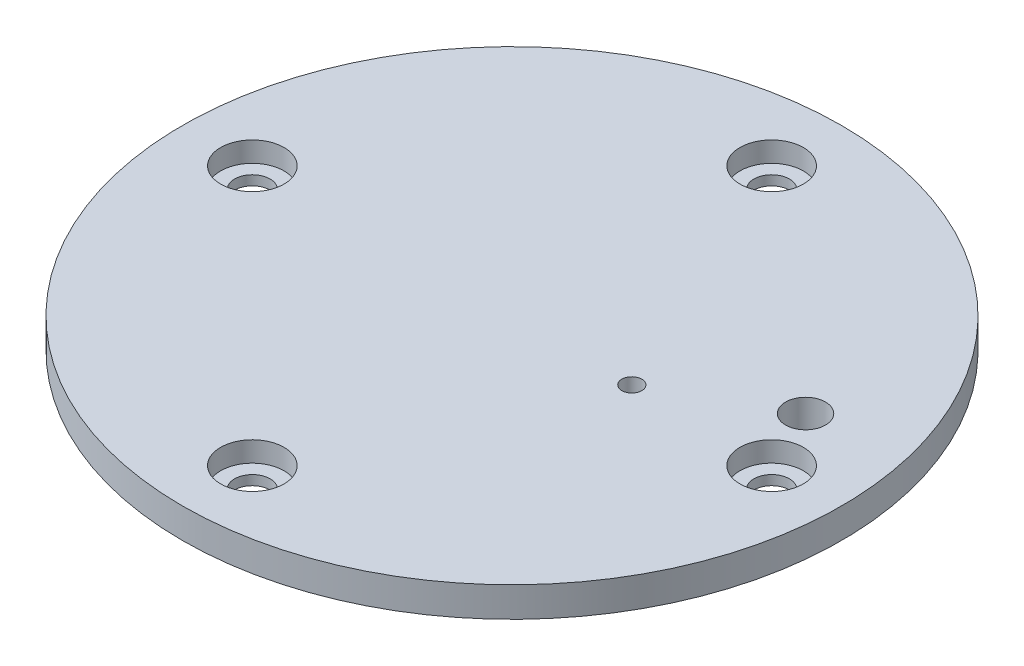
SolidWorks part; units mm, degrees
material "6061-T6 (SS)"
ref_plane "Front Plane" through (0, 0, 0) normal (0, 0, 1) x (1, 0, 0)
ref_plane "Top Plane" through (0, 0, 0) normal (0, 1, 0) x (1, 0, 0)
ref_plane "Right Plane" through (0, 0, 0) normal (1, 0, 0) x (0, 0, -1)
sketch "Sketch1" plane through (0, 0, 0) normal (0, 1, 0) x (1, 0, 0)
  circle A0 centre (0, 0) radius 16.5
  dimension "D1" = 33
extrude "Boss-Extrude1" add sketch "Sketch1" along normal blind 1.5
sketch "Sketch7" plane through (0, 1.5, 0) normal (0, 1, 0) x (1, 0, 0)
  circle A0 centre (0, -10.25) radius 0.25
  circle A1 centre (0, 0) radius 9.8
  dimension "D1" = 0.5
  dimension "D2" = 10.25
  dimension "D3" = 19.6
sketch "Sketch8" plane through (0, 1.5, 0) normal (0, 1, 0) x (1, 0, 0)
  line L0 (0, 0) -> (13.2071, 13.2071) construction
  circle A0 centre (7.7782, 7.7782) radius 1
  dimension "D1" = 2
  dimension "D2" = 11
sketch "Sketch9" plane through (0, 1.5, 0) normal (0, 1, 0) x (1, 0, 0)
  circle A0 centre (0, 0) radius 11
  dimension "D1" = 22
hole_wizard "CBORE for #0 Socket Head Cap Screw1" positions "Sketch13" profile "Sketch14" counterbore size "#0" standard "ANSI Inch" end condition through all
sketch "Sketch13" plane through (0, 1.5, 0) normal (0, 1, 0) x (1, 0, 0)
  circle A0 centre (0, 0) radius 11 construction
  point P0 (-13, 0)
  dimension "D1" = 13
sketch "Sketch14" plane through (-13, 1.5, 0) normal (1, 0, 0) x (0, 0, 1)
  line L0 (0, 0) -> (0, 1.5)
  line L1 (0, 1.5) -> (0.889, 1.5)
  line L3 (0.889, 1.5) -> (0.889, 1.016)
  line L4 (0.889, 1.016) -> (1.5875, 1.016)
  line L5 (1.5875, 1.016) -> (1.5875, 0)
  line L7 (1.5875, 0) -> (0, 0)
  line L11 (0, -6.35) -> (0, 107.95) construction
  dimension "Thru Hole Dia." = 1.778
  dimension "Thru Hole Depth" = 1.5
  dimension "C'Bore Dia." = 3.175
  dimension "C'Bore Depth" = 1.016
pattern_circular "CirPattern1" count 4 over 360 about axis through (0, 0, 0) along (0, 1, 0) of "CBORE for #0 Socket Head Cap Screw1"
sketch "Sketch15" plane through (0, 0, 0) normal (0, -1, 0) x (1, 0, 0)
  circle A0 centre (6, 0) radius 0.5
  dimension "D2" = 1
  dimension "D1" = 6
extrude "Cut-Extrude1" cut sketch "Sketch15" against normal blind 1.5
sketch "Sketch16" plane through (0, 1.5, 0) normal (0, 1, 0) x (1, 0, 0)
  line L0 (13, 0) -> (0, 0) construction
  line L1 (0, 0) -> (11.5911, 3.1058) construction
  circle A0 centre (11.5911, 3.1058) radius 1
  dimension "D1" = 2
  dimension "D2" = 12
  dimension "D3" = 15
extrude "Cut-Extrude2" cut sketch "Sketch16" against normal through all both and the other way through all
